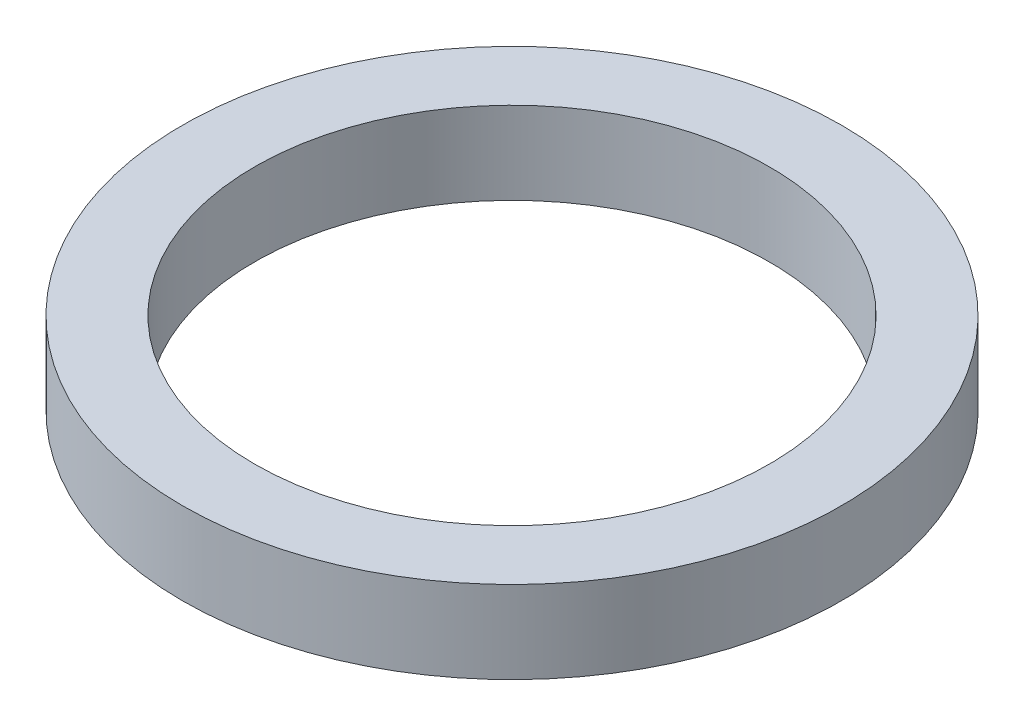
SolidWorks part; units mm, degrees
material "合金钢"
ref_plane "前视基准面" through (0, 0, 0) normal (0, 0, 1) x (1, 0, 0)
ref_plane "上视基准面" through (0, 0, 0) normal (0, 1, 0) x (1, 0, 0)
ref_plane "右视基准面" through (0, 0, 0) normal (1, 0, 0) x (0, 0, -1)
sketch "草图1" plane through (0, 0, 0) normal (0, 1, 0) x (1, 0, 0)
  circle A0 centre (0, 0) radius 12.5
  circle A1 centre (0, 0) radius 16
  dimension "D1" = 25
  dimension "D2" = 32
extrude "凸台-拉伸1" add sketch "草图1" along normal blind 4
